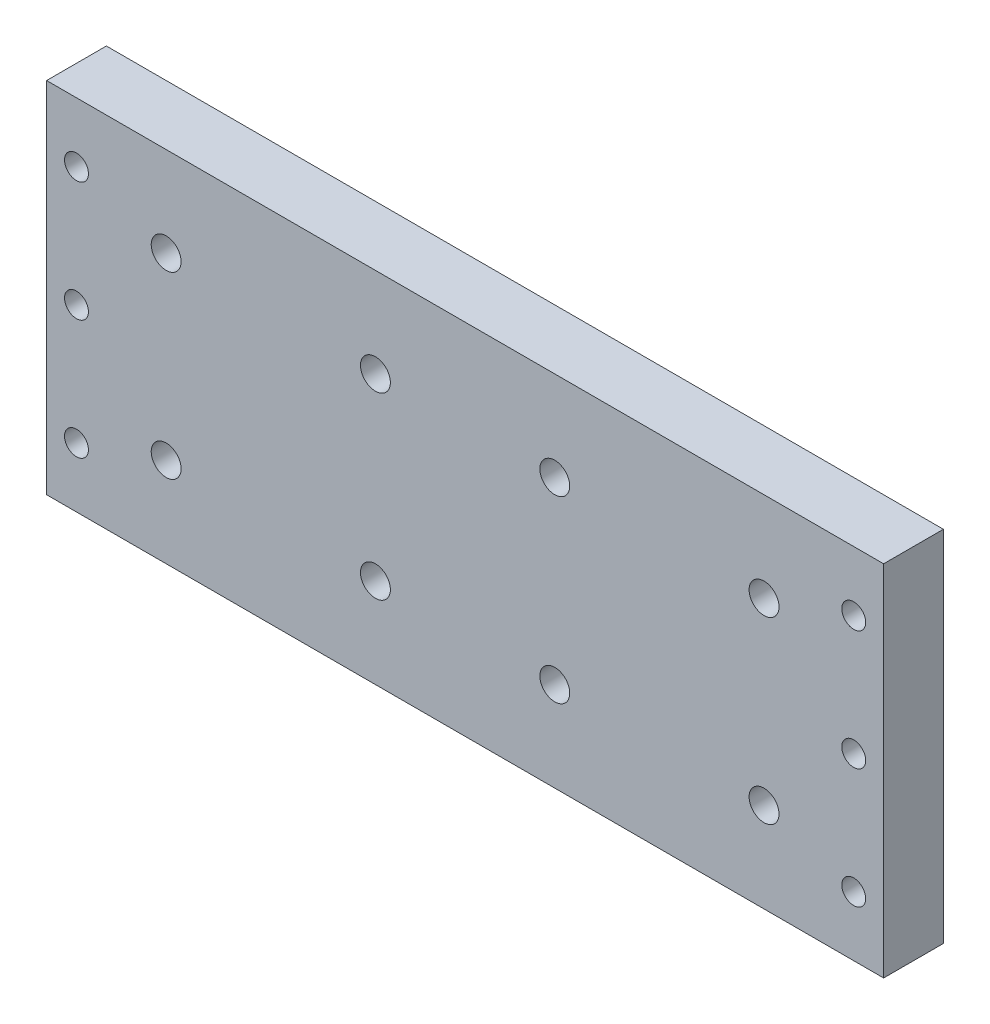
SolidWorks part; units mm, degrees
ref_plane "Спереди" through (0, 0, 0) normal (0, 0, 1) x (1, 0, 0)
ref_plane "Сверху" through (0, 0, 0) normal (0, 1, 0) x (1, 0, 0)
ref_plane "Справа" through (0, 0, 0) normal (1, 0, 0) x (0, 0, -1)
other "Configuration Table"
sketch "Эскиз1" plane through (0, 0, 0) normal (0, 0, 1) x (1, 0, 0)
  line L0 (-70, 0) -> (70, 0) construction
  line L1 (-70, -30) -> (70, -30)
  line L2 (-70, -30) -> (-70, 30)
  line L3 (-70, 30) -> (70, 30)
  line L4 (70, -30) -> (70, 30)
  line L5 (-70, -30) -> (70, 30) construction
  line L6 (-70, 30) -> (70, -30) construction
  line L7 (-65, 20) -> (-65, 0) construction
  line L8 (-65, 0) -> (-65, -20) construction
  line L9 (0, 30) -> (0, -30) construction
  line L10 (65, 0) -> (65, -20) construction
  line L11 (65, 20) -> (65, 0) construction
  circle A0 centre (-65, 0) radius 2
  circle A1 centre (-65, 20) radius 2
  circle A2 centre (-65, -20) radius 2
  circle A4 centre (65, -20) radius 2
  circle A5 centre (65, 20) radius 2
  circle A6 centre (65, 0) radius 2
  circle A7 centre (-50, 15) radius 2.5
  circle A8 centre (-50, -15) radius 2.5
  circle A9 centre (-15, 15) radius 2.5
  circle A10 centre (-15, -15) radius 2.5
  circle A11 centre (15, -15) radius 2.5
  circle A12 centre (15, 15) radius 2.5
  circle A13 centre (50, -15) radius 2.5
  circle A14 centre (50, 15) radius 2.5
  point P0 (0, 0)
  point P30 (0, 0)
  point P31 (0, 0)
  point P32 (0, 0)
  point P33 (-15, 15)
  dimension "D4" = 4
  dimension "D6" = 15
  dimension "D10" = 5
  dimension "D1" = 60
  dimension "D2" = 140
  dimension "D3" = 20
  dimension "D5" = 5
  dimension "D7" = 20
  dimension "D8" = 35
  dimension "D9" = 15
extrude "Бобышка-Вытянуть1" add sketch "Эскиз1" along normal blind 10
